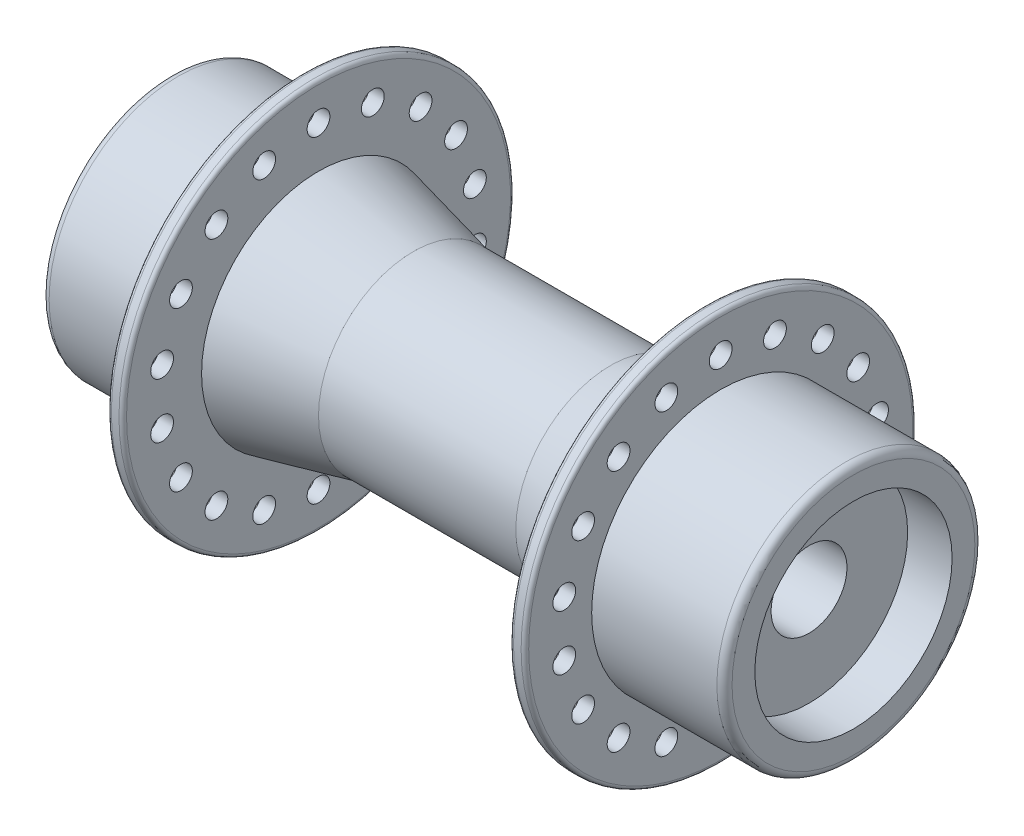
SolidWorks part; units mm, degrees
material "Cast Alloy Steel"
ref_plane "Front Plane" through (0, 0, 0) normal (0, 0, 1) x (1, 0, 0)
ref_plane "Top Plane" through (0, 0, 0) normal (0, 1, 0) x (1, 0, 0)
ref_plane "Right Plane" through (0, 0, 0) normal (1, 0, 0) x (0, 0, -1)
sketch "Sketch1" plane through (0, 0, 0) normal (0, 0, 1) x (1, 0, 0)
  line L0 (-44, 17) -> (-27.5, 17)
  line L1 (0, 0) -> (0, 77.7134) construction
  line L2 (-27.5, 17) -> (-27.5, 25.3)
  line L3 (-27, 25.8) -> (-26, 25.8)
  line L4 (13, 12.5) -> (-13, 12.5)
  line L5 (-25.5, 25.3) -> (-25.5, 15.4111)
  line L6 (-25.5, 15.4111) -> (-13, 12.5)
  line L7 (-45, 16) -> (-45, 13)
  line L8 (39.1433, 12.5) -> (39.1433, 13)
  line L9 (-39.1433, 12.5) -> (-39.1433, 5)
  line L10 (-39.1433, 5) -> (39.1433, 5)
  line L11 (39.1433, 12.5) -> (39.1433, 5)
  line L13 (45, 16) -> (45, 13)
  line L14 (25.5, 15.4111) -> (13, 12.5)
  line L15 (25.5, 25.3) -> (25.5, 15.4111)
  line L16 (27, 25.8) -> (26, 25.8)
  line L17 (27.5, 17) -> (27.5, 25.3)
  line L18 (44, 17) -> (27.5, 17)
  line L19 (0, 0) -> (7.9777, 0) construction
  line L20 (-39.1433, 12.5) -> (-39.1433, 13)
  line L21 (-39.1433, 13) -> (-45, 13)
  line L22 (39.1433, 13) -> (45, 13)
  arc A0 (-44, 17) -> (-45, 16) centre (-44, 16) ccw
  arc A1 (-25.5, 25.3) -> (-26, 25.8) centre (-26, 25.3) ccw
  arc A2 (-27, 25.8) -> (-27.5, 25.3) centre (-27, 25.3) ccw
  arc A3 (27, 25.8) -> (27.5, 25.3) centre (27, 25.3) cw
  arc A4 (25.5, 25.3) -> (26, 25.8) centre (26, 25.3) cw
  arc A5 (44, 17) -> (45, 16) centre (44, 16) cw
  point P17 (-45, 17)
  point P20 (-25.5, 25.8)
  point P23 (-27.5, 25.8)
  point P25 (0, 5)
  point P26 (0, 12.5)
  point P40 (27.5, 25.8)
  point P41 (25.5, 25.8)
  point P42 (45, 17)
  dimension "D1" = 1
  dimension "D9" = 0.5
  dimension "D2" = 17
  dimension "D3" = 8.8
  dimension "D4" = 17.5
  dimension "D5" = 2
  dimension "D6" = 12.5
  dimension "D7" = 12.5
  dimension "D8" = 5
  dimension "D10" = 0.5
  dimension "D11" = 0.5
revolve "Revolve1" add sketch "Sketch1" angle 360 about L19
sketch "Sketch2" plane through (27.5, 0, 0) normal (1, 0, 0) x (0, 0, -1)
  line L0 (0, 0) -> (0, 20.9304) construction
  circle A0 centre (0, 20.9304) radius 1.5
  dimension "D1" = 3
extrude "Cut-Extrude1" cut sketch "Sketch2" against normal up to next
pattern_circular "CirPattern1" count 18 over 360 about axis through (0, 0, 0) along (1, 0, 0) of "Cut-Extrude1"
mirror "Mirror1" about plane through (0, 0, 0) normal (1, 0, 0) of "CirPattern1", "Cut-Extrude1"
